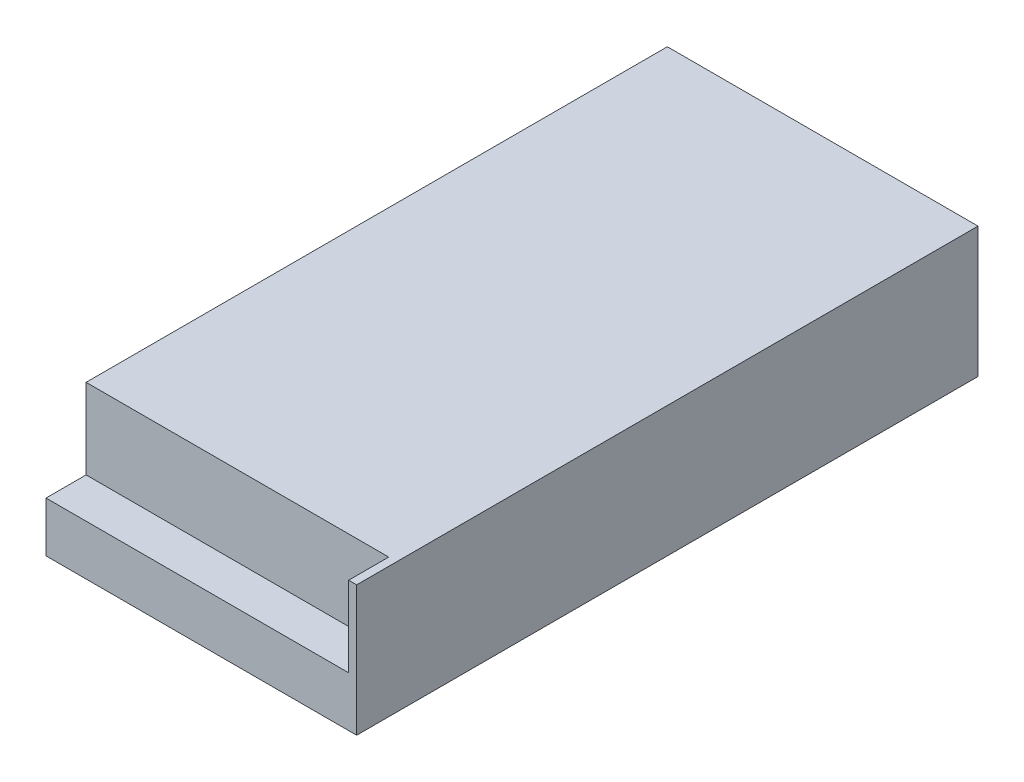
SolidWorks part; units mm, degrees
ref_plane "Front Plane" through (0, 0, 0) normal (0, 0, 1) x (1, 0, 0)
ref_plane "Top Plane" through (0, 0, 0) normal (0, 1, 0) x (1, 0, 0)
ref_plane "Right Plane" through (0, 0, 0) normal (1, 0, 0) x (0, 0, -1)
sketch "Sketch1" plane through (0, 0, 0) normal (0, 1, 0) x (1, 0, 0)
  line L1 (0, 0) -> (98.425, 0)
  line L2 (0, 0) -> (0, 196.85)
  line L3 (0, 196.85) -> (98.425, 196.85)
  line L4 (98.425, 0) -> (98.425, 196.85)
  dimension "D1" = 98.425
  dimension "D2" = 196.85
extrude "Boss-Extrude1" add sketch "Sketch1" along normal blind 41.275
sketch "Sketch2" plane through (98.425, 0, 0) normal (1, 0, 0) x (0, 0, -1)
  line L0 (0, 41.275) -> (0, 0) construction
  line L1 (0, 41.275) -> (12.7, 41.275)
  line L2 (0, 41.275) -> (0, 15.875)
  line L3 (0, 15.875) -> (12.7, 15.875)
  line L4 (12.7, 41.275) -> (12.7, 15.875)
  line L5 (0, 41.275) -> (196.85, 41.275) construction
  dimension "D1" = 12.7
  dimension "D2" = 25.4
extrude "Cut-Extrude1" cut sketch "Sketch2" along normal offset from surface (95.885 mm away) 2.54 from surface at -98.425 up to face at (98.425, 20.6375, -98.425) starting at face at (0, 20.6375, -98.425)
